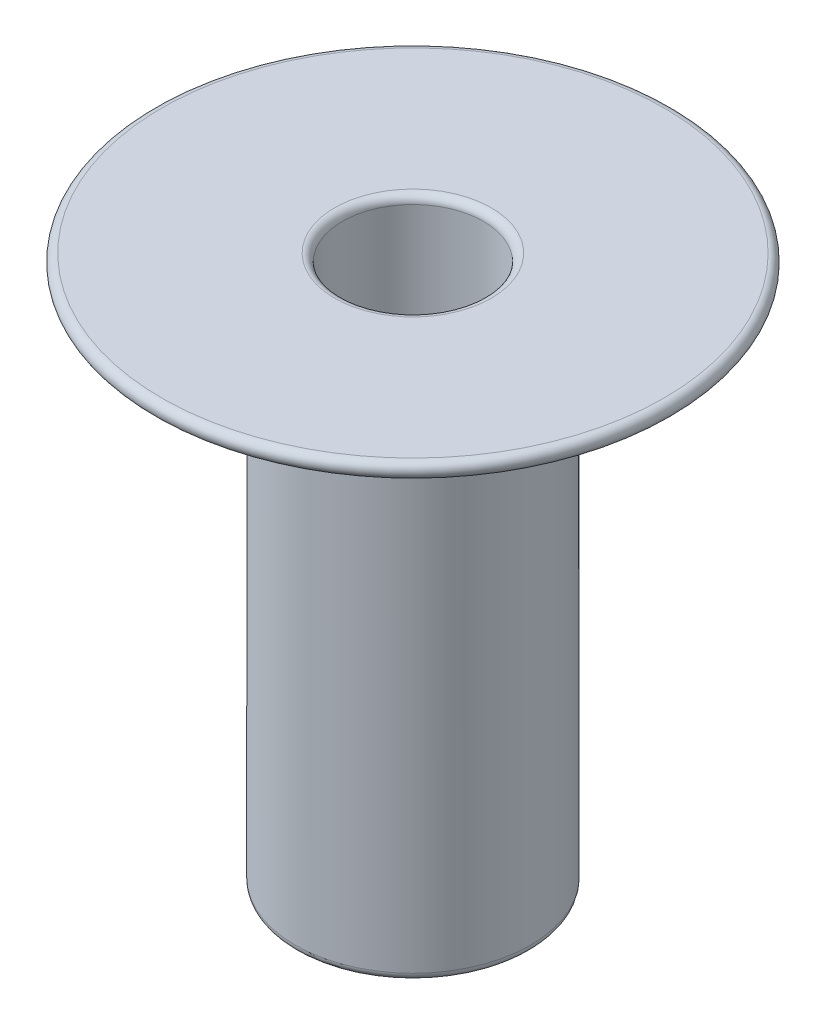
SolidWorks part; units mm, degrees
material "1350 合金"
ref_plane "前视基准面" through (0, 0, 0) normal (0, 0, 1) x (1, 0, 0)
ref_plane "上视基准面" through (0, 0, 0) normal (0, 1, 0) x (1, 0, 0)
ref_plane "右视基准面" through (0, 0, 0) normal (1, 0, 0) x (0, 0, -1)
sketch "草图1" plane through (0, 0, 0) normal (0, 0, 1) x (1, 0, 0)
  line L0 (-0.9, 2.4) -> (-3.5785, 2.4)
  line L1 (-3.5785, 2.4) -> (-1.5, 1.2)
  line L2 (-1.5, 1.2) -> (-1.5, -4.6)
  line L3 (-1.5, -4.6) -> (0, -4.6)
  line L4 (0, -1000) -> (0, 49000) construction
  line L5 (-0.9, 2.4) -> (-0.9, 0)
  line L6 (-0.9, 0) -> (0, 0)
  line L7 (-1.5, 1.2) -> (-0.9, 1.2) construction
  line L8 (0, -4.6) -> (0, 0)
  dimension "D1" = 120
  dimension "d" = 3
  dimension "dk" = 7.1569
  dimension "dl" = 1.8
  dimension "K" = 1.2
  dimension "L" = 7
revolve "旋转1" add sketch "草图1" angle 360 about L8
fillet "圆角1" radius 0.1 4 edges at (0.9, 0, 0) (0.9, 2.4, 0) (3.5785, 2.4, 0) (1.5, -4.6, 0)
other "冻结***"
